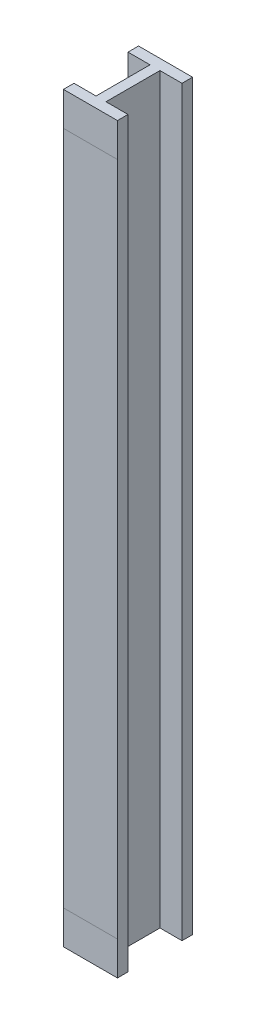
SolidWorks part; units mm, degrees
ref_plane "Płaszczyzna przednia" through (0, 0, 0) normal (0, 0, 1) x (1, 0, 0)
ref_plane "Płaszczyzna górna" through (0, 0, 0) normal (0, 1, 0) x (1, 0, 0)
ref_plane "Płaszczyzna prawa" through (0, 0, 0) normal (1, 0, 0) x (0, 0, -1)
sketch "Szkic1" plane through (0, 0, 0) normal (0, 1, 0) x (1, 0, 0)
  line L0 (0, 0) -> (80, 0)
  line L1 (80, 0) -> (80, 31.25)
  line L2 (80, 31.25) -> (14.7486, 31.25)
  line L3 (14.7486, 31.25) -> (14.7486, 191.25)
  line L4 (14.7486, 191.25) -> (80, 191.25)
  line L5 (80, 191.25) -> (80, 222.5)
  line L6 (80, 222.5) -> (-80, 222.5)
  line L7 (-80, 222.5) -> (-80, 191.25)
  line L8 (-80, 191.25) -> (-14.7486, 191.25)
  line L9 (-14.7486, 191.25) -> (-14.7486, 31.25)
  line L10 (-14.7486, 31.25) -> (-80, 31.25)
  line L11 (-80, 31.25) -> (-80, 0)
  line L12 (-80, 0) -> (0, 0)
  point P12 (0, 0)
  dimension "D1" = 160
  dimension "D2" = 65.2514
  dimension "D3" = 160
  dimension "D4" = 222.5
extrude "Dodanie-wyciągnięcie1" add sketch "Szkic1" along normal blind 2200
sketch "Szkic2" plane through (0, 0, 0) normal (0, 0, 1) x (1, 0, 0)
  line L0 (-80, 2100) -> (80, 2100)
  line L1 (-80, 2200) -> (-80, 0) construction
  line L2 (80, 2200) -> (80, 0) construction
  line L3 (-80, 100) -> (80, 100)
  line L4 (-80, 2200) -> (80, 2200) construction
  line L5 (-80, 0) -> (80, 0) construction
  dimension "D1" = 100
  dimension "D2" = 100
split line "Linia podziałowa1"
